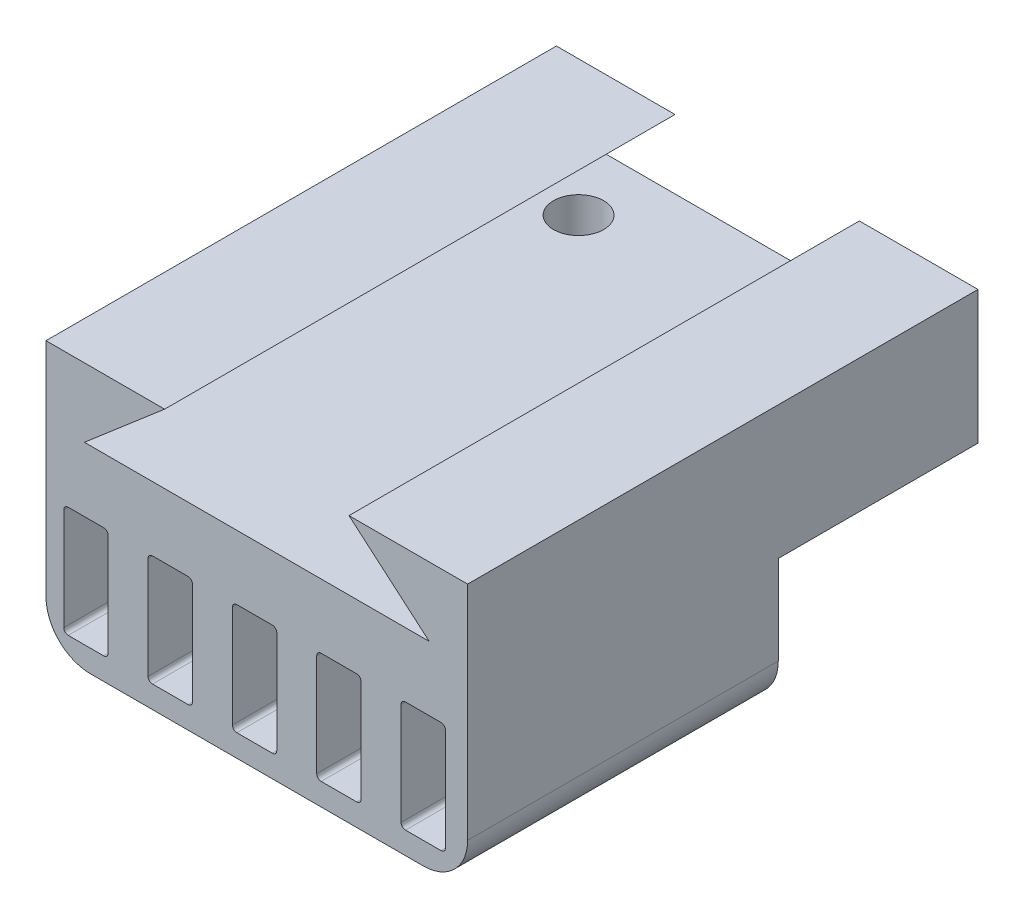
SolidWorks part; units mm, degrees
material "PLA"
ref_plane "Front" through (0, 0, 0) normal (0, 0, 1) x (1, 0, 0)
ref_plane "Top" through (0, 0, 0) normal (0, 1, 0) x (1, 0, 0)
ref_plane "Right" through (0, 0, 0) normal (1, 0, 0) x (0, 0, -1)
sketch "Sketch1" plane through (0, 0, 0) normal (0, 0, 1) x (1, 0, 0)
  line L0 (5.08, -21.59) -> (-5.08, -21.59)
  line L5 (-5.1627, -21.4936) -> (5.1627, -21.4936)
  line L6 (-5.1627, -21.4936) -> (-9.8683, -25.527)
  line L7 (-9.8683, -25.527) -> (9.8683, -25.527)
  line L8 (9.8683, -25.527) -> (5.1627, -21.4936)
  line L9 (-5.08, -21.59) -> (-5.2751, -21.59)
  line L10 (5.08, -21.59) -> (5.2751, -21.59)
  line L11 (-5.08, -21.59) -> (-5.2751, -21.59)
  line L12 (9.525, -21.59) -> (9.525, -17.6598)
  line L13 (5.08, -21.59) -> (9.525, -21.59)
  line L14 (9.525, -25.4) -> (5.08, -21.59)
  line L15 (-9.525, -25.4) -> (9.525, -25.4)
  line L16 (-5.08, -21.59) -> (-9.525, -25.4)
  line L17 (-9.525, -21.59) -> (-5.08, -21.59)
  line L18 (-9.525, -17.6598) -> (-9.525, -21.59)
  line L19 (9.525, -21.59) -> (9.525, -17.6598)
  line L20 (5.08, -21.59) -> (9.525, -21.59)
  line L21 (9.525, -25.4) -> (5.08, -21.59)
  line L22 (-9.525, -25.4) -> (9.525, -25.4)
  line L23 (-5.08, -21.59) -> (-9.525, -25.4)
  line L24 (-9.525, -21.59) -> (-5.08, -21.59)
  line L25 (-9.525, -17.6598) -> (-9.525, -21.59)
  line L27 (-12.065, -29.21) -> (12.065, -29.21)
  line L28 (-12.065, -29.21) -> (-12.065, -21.59)
  line L29 (-12.065, -21.59) -> (12.065, -21.59)
  line L30 (12.065, -29.21) -> (12.065, -21.59)
  arc A2 (-20.6375, -11.1054) -> (-19.2555, -10.6965) centre (-20.6375, -8.5654) ccw
  arc A3 (19.2555, -10.6965) -> (20.6375, -11.1054) centre (20.6375, -8.5654) ccw
  arc A4 (-20.6375, -11.1054) -> (-19.2555, -10.6965) centre (-20.6375, -8.5654) ccw
  arc A5 (19.2555, -10.6965) -> (20.6375, -11.1054) centre (20.6375, -8.5654) ccw
  ellipse E2 centre (0, 0) end of major axis (25.4, 0) minor radius 19.05 (-20.6375, -11.1054) -> (-9.525, -17.6598) ccw
  ellipse E3 centre (0, 0) end of major axis (25.4, 0) minor radius 19.05 (9.525, -17.6598) -> (20.6375, -11.1054) ccw
  ellipse E4 centre (0, 0) end of major axis (25.4, 0) minor radius 19.05 (-20.6375, -11.1054) -> (-9.525, -17.6598) ccw
  ellipse E5 centre (0, 0) end of major axis (25.4, 0) minor radius 19.05 (9.525, -17.6598) -> (20.6375, -11.1054) ccw
  spline S1 degree 3 poles (-2166.445, -15849.0793) (-418.6607, -134.144) (57.4604, 23.5329) (18.4102, -11.4784) (18.1685, -11.6861) (17.4022, -12.3125) (16.8339, -12.7373) (15.8949, -13.3659) (15.5674, -13.5742) (14.8823, -13.9857) (14.5239, -14.1894) (13.7828, -14.586) (13.3995, -14.7793) (12.6066, -15.1542) (12.1964, -15.336) (11.3542, -15.6842) (10.9219, -15.8506) (10.0343, -16.1671) (9.5775, -16.3175) (8.1859, -16.7374) (7.2281, -16.9768) (5.7448, -17.2706) (5.2427, -17.3576) (4.2222, -17.5087) (3.7022, -17.5728) (2.6581, -17.6756) (2.1332, -17.7144) (1.0777, -17.7665) (0.5456, -17.7797) (-1.0381, -17.7806) (-2.0822, -17.7301) (-3.6313, -17.5808) (-4.1449, -17.5187) (-5.1662, -17.3701) (-5.6756, -17.2832) (-6.6756, -17.0872) (-7.1675, -16.9781) (-8.1355, -16.7387) (-8.6125, -16.608) (-9.5437, -16.3283) (-9.9984, -16.1792) (-10.887, -15.8637) (-11.3215, -15.697) (-12.5878, -15.1754) (-13.3817, -14.7994) (-14.8691, -14.0059) (-15.5563, -13.5917) (-16.8227, -12.7456) (-17.3958, -12.3175) (-61.9722, 24.1081) (359.4859, -21.3348) (4215.4566, -15431.1683) knots -5.38 -5.38 -5.38 -5.38 0.03125 0.03125 0.0625 0.0625 0.125 0.125 0.15625 0.15625 0.1875 0.1875 0.21875 0.21875 0.25 0.25 0.28125 0.28125 0.3125 0.3125 0.375 0.375 0.40625 0.40625 0.4375 0.4375 0.46875 0.46875 0.5 0.5 0.5625 0.5625 0.59375 0.59375 0.625 0.625 0.65625 0.65625 0.6875 0.6875 0.71875 0.71875 0.75 0.75 0.8125 0.8125 0.875 0.875 0.9375 0.9375 6.300617 6.300617 6.300617 6.300617 only from (19.2555, -10.6965) to (-19.2555, -10.6965)
  spline S2 degree 3 poles (19.2555, -10.6965) (19.0657, -10.8817) (18.8587, -11.0763) (18.4102, -11.4784) (18.1685, -11.6861) (17.4022, -12.3125) (16.8339, -12.7373) (15.8949, -13.3659) (15.5674, -13.5742) (14.8823, -13.9857) (14.5239, -14.1894) (13.7828, -14.586) (13.3995, -14.7793) (12.6066, -15.1542) (12.1964, -15.336) (11.3542, -15.6842) (10.9219, -15.8506) (10.0343, -16.1671) (9.5775, -16.3175) (8.1859, -16.7374) (7.2281, -16.9768) (5.7448, -17.2706) (5.2427, -17.3576) (4.2222, -17.5087) (3.7022, -17.5728) (2.6581, -17.6756) (2.1332, -17.7144) (1.0777, -17.7665) (0.5456, -17.7797) (-1.0381, -17.7806) (-2.0822, -17.7301) (-3.6313, -17.5808) (-4.1449, -17.5187) (-5.1662, -17.3701) (-5.6756, -17.2832) (-6.6756, -17.0872) (-7.1675, -16.9781) (-8.1355, -16.7387) (-8.6125, -16.608) (-9.5437, -16.3283) (-9.9984, -16.1792) (-10.887, -15.8637) (-11.3215, -15.697) (-12.5878, -15.1754) (-13.3817, -14.7994) (-14.8691, -14.0059) (-15.5563, -13.5917) (-16.8227, -12.7456) (-17.3958, -12.3175) (-18.4228, -11.4783) (-18.8731, -11.0698) (-19.2555, -10.6965) knots 0 0 0 0 0.03125 0.03125 0.0625 0.0625 0.125 0.125 0.15625 0.15625 0.1875 0.1875 0.21875 0.21875 0.25 0.25 0.28125 0.28125 0.3125 0.3125 0.375 0.375 0.40625 0.40625 0.4375 0.4375 0.46875 0.46875 0.5 0.5 0.5625 0.5625 0.59375 0.59375 0.625 0.625 0.65625 0.65625 0.6875 0.6875 0.71875 0.71875 0.75 0.75 0.8125 0.8125 0.875 0.875 0.9375 0.9375 1 1 1 1
  dimension "D1" = 0
  dimension "D2" = 2.54
  dimension "D3" = 2.54
  dimension "D4" = 7.62
  dimension "D5" = 0.127
extrude "Boss-Extrude2" add sketch "Sketch1" along normal blind 25.4 contours L27 L30 L29 L20 L8 L7 L6 L24 L28
sketch "Sketch3" plane through (0, -29.21, 0) normal (0, -1, 0) x (-1, 0, 0)
  line L0 (12.065, -25.4) -> (12.065, 0) construction
  line L1 (-12.065, -25.4) -> (12.065, -25.4)
  line L2 (-12.065, -25.4) -> (-12.065, -7.62)
  line L3 (-12.065, -7.62) -> (12.065, -7.62)
  line L4 (12.065, -25.4) -> (12.065, -7.62)
  dimension "D1" = 17.78
extrude "Boss-Extrude3" add sketch "Sketch3" along normal blind 7.62
sketch "Sketch4" plane through (0, 0, 25.4) normal (0, 0, 1) x (1, 0, 0)
  line L0 (12.065, -36.83) -> (-12.065, -36.83) construction
  line L1 (10.541, -35.56) -> (8.509, -35.56)
  line L2 (10.795, -35.306) -> (10.795, -29.464)
  line L3 (10.541, -29.21) -> (8.509, -29.21)
  line L4 (8.255, -35.306) -> (8.255, -29.464)
  line L5 (12.065, -36.83) -> (12.065, -21.59) construction
  line L6 (5.969, -35.306) -> (5.969, -29.464)
  line L7 (5.715, -35.56) -> (3.683, -35.56)
  line L8 (3.429, -35.306) -> (3.429, -29.464)
  line L9 (5.715, -29.21) -> (3.683, -29.21)
  line L10 (1.143, -35.306) -> (1.143, -29.464)
  line L11 (0.889, -35.56) -> (-1.143, -35.56)
  line L12 (-1.397, -35.306) -> (-1.397, -29.464)
  line L13 (0.889, -29.21) -> (-1.143, -29.21)
  line L14 (-3.683, -35.306) -> (-3.683, -29.464)
  line L15 (-3.937, -35.56) -> (-5.969, -35.56)
  line L16 (-6.223, -35.306) -> (-6.223, -29.464)
  line L17 (-3.937, -29.21) -> (-5.969, -29.21)
  line L18 (-8.509, -35.306) -> (-8.509, -29.464)
  line L19 (-8.763, -35.56) -> (-10.795, -35.56)
  line L20 (-11.049, -35.306) -> (-11.049, -29.464)
  line L21 (-8.763, -29.21) -> (-10.795, -29.21)
  arc A0 (8.509, -29.21) -> (8.255, -29.464) centre (8.509, -29.464) ccw
  arc A1 (10.795, -29.464) -> (10.541, -29.21) centre (10.541, -29.464) ccw
  arc A2 (8.509, -35.56) -> (8.255, -35.306) centre (8.509, -35.306) cw
  arc A3 (10.541, -35.56) -> (10.795, -35.306) centre (10.541, -35.306) ccw
  arc A4 (5.715, -35.56) -> (5.969, -35.306) centre (5.715, -35.306) ccw
  arc A5 (5.969, -29.464) -> (5.715, -29.21) centre (5.715, -29.464) ccw
  arc A6 (3.683, -35.56) -> (3.429, -35.306) centre (3.683, -35.306) cw
  arc A7 (3.683, -29.21) -> (3.429, -29.464) centre (3.683, -29.464) ccw
  arc A8 (0.889, -35.56) -> (1.143, -35.306) centre (0.889, -35.306) ccw
  arc A9 (1.143, -29.464) -> (0.889, -29.21) centre (0.889, -29.464) ccw
  arc A10 (-1.143, -35.56) -> (-1.397, -35.306) centre (-1.143, -35.306) cw
  arc A11 (-1.143, -29.21) -> (-1.397, -29.464) centre (-1.143, -29.464) ccw
  arc A12 (-3.937, -35.56) -> (-3.683, -35.306) centre (-3.937, -35.306) ccw
  arc A13 (-3.683, -29.464) -> (-3.937, -29.21) centre (-3.937, -29.464) ccw
  arc A14 (-5.969, -35.56) -> (-6.223, -35.306) centre (-5.969, -35.306) cw
  arc A15 (-5.969, -29.21) -> (-6.223, -29.464) centre (-5.969, -29.464) ccw
  arc A16 (-8.763, -35.56) -> (-8.509, -35.306) centre (-8.763, -35.306) ccw
  arc A17 (-8.509, -29.464) -> (-8.763, -29.21) centre (-8.763, -29.464) ccw
  arc A18 (-10.795, -35.56) -> (-11.049, -35.306) centre (-10.795, -35.306) cw
  arc A19 (-10.795, -29.21) -> (-11.049, -29.464) centre (-10.795, -29.464) ccw
  point P12 (10.795, -29.21)
  point P15 (8.255, -35.56)
  point P18 (10.795, -35.56)
  dimension "D5" = 0.254
  dimension "D1" = 2.54
  dimension "D2" = 6.35
  dimension "D3" = 1.27
  dimension "D4" = 1.27
  dimension "D6" = 5
extrude "Cut-Extrude2" cut sketch "Sketch4" against normal offset from surface (16.51 mm away) 1.27 up to face at (0, -33.02, 7.62)
sketch "Sketch5" plane through (0, 0, 8.89) normal (0, 0, 1) x (1, 0, 0)
  line L3 (10.541, -29.21) -> (8.509, -29.21) construction
  line L8 (10.795, -35.306) -> (10.795, -29.464) construction
  circle A0 centre (9.525, -32.385) radius 0.9525
  circle A1 centre (4.699, -32.385) radius 0.9525
  circle A2 centre (-0.127, -32.385) radius 0.9525
  circle A3 centre (-4.953, -32.385) radius 0.9525
  circle A4 centre (-9.779, -32.385) radius 0.9525
  dimension "D1" = 1.905
  dimension "D2" = 3.175
  dimension "D3" = 1.27
  dimension "D4" = 5
extrude "Cut-Extrude3" cut sketch "Sketch5" against normal blind 1.27
fillet "Fillet1" radius 2.54 2 edges at (-12.065, -36.83, 16.51) (12.065, -36.83, 16.51)
sketch "Sketch6" plane through (0, 0, 0) normal (0, 0, -1) x (-1, 0, 0)
  line L8 (-12.065, -29.21) -> (12.065, -29.21)
  line L9 (12.065, -29.21) -> (12.065, -21.59)
  line L10 (12.065, -21.59) -> (5.2751, -21.59)
  line L11 (5.2751, -21.59) -> (9.8683, -25.527)
  line L12 (9.8683, -25.527) -> (-9.8683, -25.527)
  line L13 (-9.8683, -25.527) -> (-5.2751, -21.59)
  line L14 (-5.2751, -21.59) -> (-12.065, -21.59)
  line L15 (-12.065, -21.59) -> (-12.065, -29.21)
  line L16 (-12.065, -29.21) -> (12.065, -29.21)
  line L17 (12.065, -29.21) -> (12.065, -21.59)
  line L18 (12.065, -21.59) -> (5.2751, -21.59)
  line L19 (5.2751, -21.59) -> (9.8683, -25.527)
  line L20 (9.8683, -25.527) -> (-9.8683, -25.527)
  line L21 (-9.8683, -25.527) -> (-5.2751, -21.59)
  line L22 (-5.2751, -21.59) -> (-12.065, -21.59)
  line L23 (-12.065, -21.59) -> (-12.065, -29.21)
  dimension "D1" = 0
extrude "Boss-Extrude4" add sketch "Sketch6" along normal blind 3.81
sketch "Sketch2" plane through (0, -29.21, 0) normal (0, -1, 0) x (-1, 0, 0)
  line L1 (-12.065, 3.81) -> (12.065, 3.81) construction
  line L2 (-12.065, -7.62) -> (-12.065, 3.81) construction
  line L3 (12.065, -7.62) -> (12.065, 3.81) construction
  circle A0 centre (-6.985, 0) radius 1.4351
  circle A1 centre (6.985, 0) radius 1.4351
  point P8 (-12.065, -5.4045)
  dimension "D1" = 2.8702
  dimension "D3" = 5.08
  dimension "D5" = 5.08
  dimension "D2" = 3.81
  dimension "D4" = 3.81
extrude "Cut-Extrude1" cut sketch "Sketch2" against normal up to surface (3.683 mm away) up to face at (0, -25.527, 10.795)
